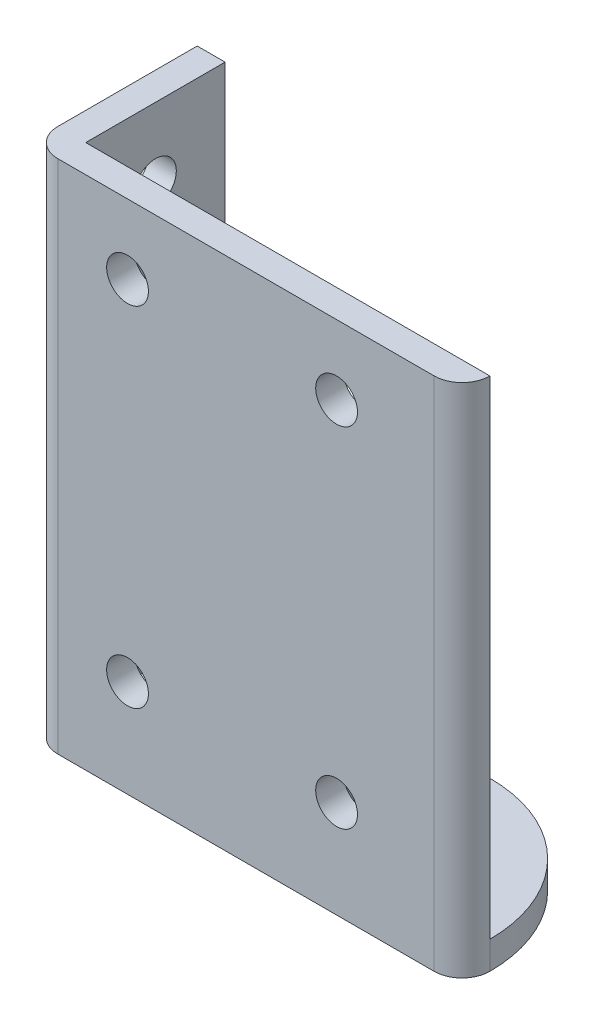
SolidWorks part; units mm, degrees
ref_plane "Front Plane" through (0, 0, 0) normal (0, 0, 1) x (1, 0, 0)
ref_plane "Top Plane" through (0, 0, 0) normal (0, 1, 0) x (1, 0, 0)
ref_plane "Right Plane" through (0, 0, 0) normal (1, 0, 0) x (0, 0, -1)
sketch "Sketch1" plane through (0, 0, 0) normal (0, 1, 0) x (1, 0, 0)
  line L0 (0, 4) -> (0, 24)
  line L1 (0, 24) -> (42, 24)
  line L2 (4, 0) -> (58, 0)
  arc A0 (0, 4) -> (4, 0) centre (4, 4) ccw
  arc A1 (42, 24) -> (62, 4) centre (42, 4) cw
  arc A2 (62, 4) -> (58, 0) centre (58, 4) cw
  point P8 (0, 0)
  dimension "D1" = 4
  dimension "D2" = 20
  dimension "D3" = 4
  dimension "D4" = 62
  dimension "D5" = 24
extrude "Boss-Extrude1" add sketch "Sketch1" along normal blind 4
sketch "Sketch2" plane through (0, 4, 0) normal (0, 1, 0) x (1, 0, 0)
  line L2 (4, 24) -> (4, 4)
  line L3 (42, 24) -> (0, 24) construction
  line L4 (4, 4) -> (62, 4)
  line L5 (0, 24) -> (0, 4) construction
  line L6 (4, 0) -> (58, 0) construction
  line L10 (42, 24) -> (0, 24)
  line L11 (0, 24) -> (0, 4)
  line L12 (4, 0) -> (58, 0)
  line L13 (4, 24) -> (0, 24)
  line L14 (0, 24) -> (0, 4)
  line L15 (4, 0) -> (58, 0)
  arc A4 (0, 4) -> (4, 0) centre (4, 4) ccw
  arc A5 (58, 0) -> (62, 4) centre (58, 4) ccw
  arc A6 (62, 4) -> (42, 24) centre (42, 4) ccw
  arc A7 (0, 4) -> (4, 0) centre (4, 4) ccw
  arc A8 (58, 0) -> (62, 4) centre (58, 4) ccw
  dimension "D1" = 4
  dimension "D2" = 4
  dimension "D3" = 0
extrude "Boss-Extrude2" add sketch "Sketch2" along normal blind 70
sketch "Sketch3" plane through (0, 4, 0) normal (0, 1, 0) x (1, 0, 0)
  line L0 (4, 4) -> (4, 24) construction
  line L1 (62, 4) -> (4, 4) construction
  circle A0 centre (34, 14) radius 3
  dimension "D1" = 6
  dimension "D2" = 30
  dimension "D3" = 10
extrude "Cut-Extrude1" cut sketch "Sketch3" against normal through all
sketch "Sketch4" plane through (4, 0, 0) normal (1, 0, 0) x (0, 0, -1)
  line L0 (4, 74) -> (24, 74) construction
  line L1 (4, 4) -> (24, 4) construction
  circle A0 centre (14, 64) radius 3
  circle A1 centre (14, 14) radius 3
  point P6 (14, 74)
  dimension "D1" = 6
  dimension "D2" = 10
  dimension "D3" = 10
extrude "Cut-Extrude2" cut sketch "Sketch4" against normal through all
sketch "Sketch6" plane through (0, 0, -4) normal (0, 0, -1) x (-1, 0, 0)
  line L0 (-4, 74) -> (-4, 4) construction
  line L1 (-42, 4) -> (-4, 4) construction
  line L2 (-14, 14) -> (-44, 14) construction
  line L3 (-14, 14) -> (-14, 64) construction
  circle A0 centre (-14, 14) radius 3
  circle A1 centre (-44, 14) radius 3
  circle A2 centre (-14, 64) radius 3
  circle A3 centre (-44, 64) radius 3
  dimension "D1" = 6
  dimension "D2" = 10
  dimension "D3" = 10
  dimension "D6" = 30
  dimension "D7" = 50
  dimension "D4" = 2
  dimension "D5" = 2
extrude "Cut-Extrude3" cut sketch "Sketch6" against normal through all
